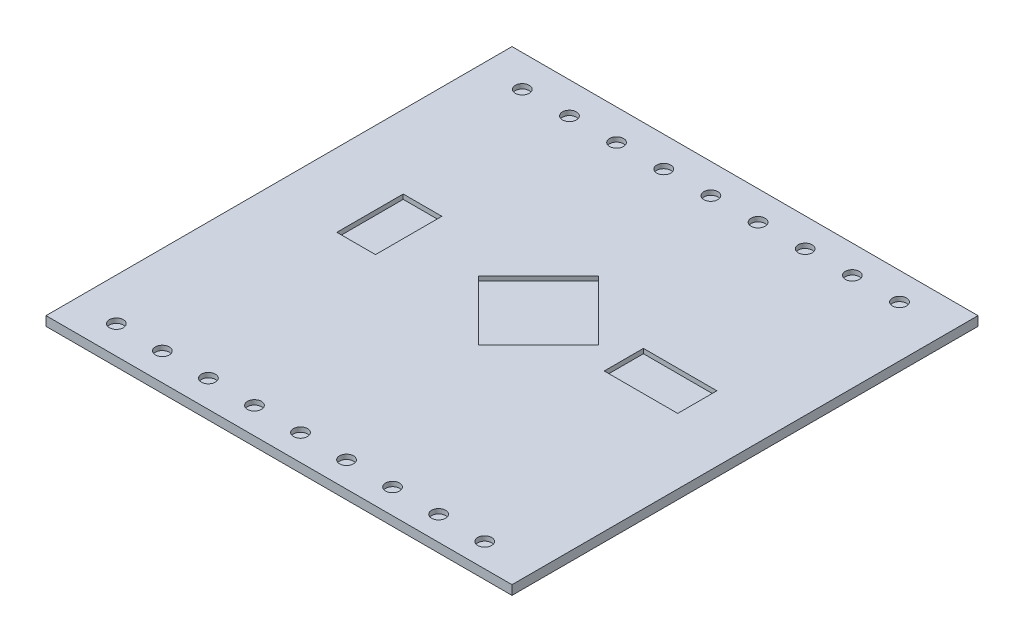
SolidWorks part; units mm, degrees
ref_plane "Front Plane" through (0, 0, 0) normal (0, 0, 1) x (1, 0, 0)
ref_plane "Top Plane" through (0, 0, 0) normal (0, 1, 0) x (1, 0, 0)
ref_plane "Right Plane" through (0, 0, 0) normal (1, 0, 0) x (0, 0, -1)
sketch "Sketch1" plane through (0, 0, 0) normal (0, 0, 1) x (1, 0, 0)
  line L1 (5, -0.1) -> (-5, -0.1)
  line L2 (5, -0.1) -> (5, 0.1)
  line L3 (5, 0.1) -> (-5, 0.1)
  line L4 (-5, -0.1) -> (-5, 0.1)
  line L5 (5, -0.1) -> (-5, 0.1) construction
  line L6 (5, 0.1) -> (-5, -0.1) construction
  point P0 (0, 0)
  dimension "D1" = 10
  dimension "D2" = 0.2
extrude "Boss-Extrude1" add sketch "Sketch1" along normal blind 10
sketch "Sketch2" plane through (0, 0.1, 0) normal (0, 1, 0) x (1, 0, 0)
  line L0 (1.4761, -4.6189) -> (0.1898, -3.3326)
  line L1 (0.1898, -3.3326) -> (-1.0966, -4.6189)
  line L2 (-1.0966, -4.6189) -> (0.1898, -5.9053)
  line L3 (0.1898, -5.9053) -> (1.4761, -4.6189)
  line L5 (-2.5983, -3.9068) -> (-3.4275, -3.9068)
  line L6 (-2.5983, -3.9068) -> (-2.5983, -5.3311)
  line L7 (-2.5983, -5.3311) -> (-3.4275, -5.3311)
  line L8 (-3.4275, -3.9068) -> (-3.4275, -5.3311)
  line L9 (-2.5983, -3.9068) -> (-3.4275, -5.3311) construction
  line L10 (-2.5983, -5.3311) -> (-3.4275, -3.9068) construction
  line L11 (3.5952, -4.1983) -> (2.0185, -4.1983)
  line L12 (3.5952, -4.1983) -> (3.5952, -5.0396)
  line L13 (3.5952, -5.0396) -> (2.0185, -5.0396)
  line L14 (2.0185, -4.1983) -> (2.0185, -5.0396)
  line L15 (3.5952, -4.1983) -> (2.0185, -5.0396) construction
  line L16 (3.5952, -5.0396) -> (2.0185, -4.1983) construction
  circle A0 centre (3.904, -0.5884) radius 0.15
  circle A1 centre (2.904, -0.6003) radius 0.15
  circle A2 centre (1.9041, -0.6122) radius 0.15
  circle A3 centre (0.9042, -0.6241) radius 0.15
  circle A4 centre (-0.0958, -0.6361) radius 0.15
  circle A5 centre (-1.0957, -0.648) radius 0.15
  circle A6 centre (-2.0956, -0.6599) radius 0.15
  circle A7 centre (-3.0955, -0.6718) radius 0.15
  circle A8 centre (-4.0955, -0.6837) radius 0.15
  circle A9 centre (-4.0955, -9.3955) radius 0.15
  circle A10 centre (-3.0955, -9.4074) radius 0.15
  circle A11 centre (-2.0956, -9.4193) radius 0.15
  circle A12 centre (-1.0957, -9.4312) radius 0.15
  circle A13 centre (0.9042, -9.455) radius 0.15
  circle A14 centre (-0.0958, -9.4431) radius 0.15
  circle A15 centre (1.9041, -9.4669) radius 0.15
  circle A16 centre (2.904, -9.4788) radius 0.15
  circle A17 centre (3.904, -9.4907) radius 0.15
  point P2 (-3.0129, -4.6189)
  point P9 (2.8069, -4.6189)
  dimension "D1" = 9
extrude "Cut-Extrude1" cut sketch "Sketch2" against normal blind 0.1
